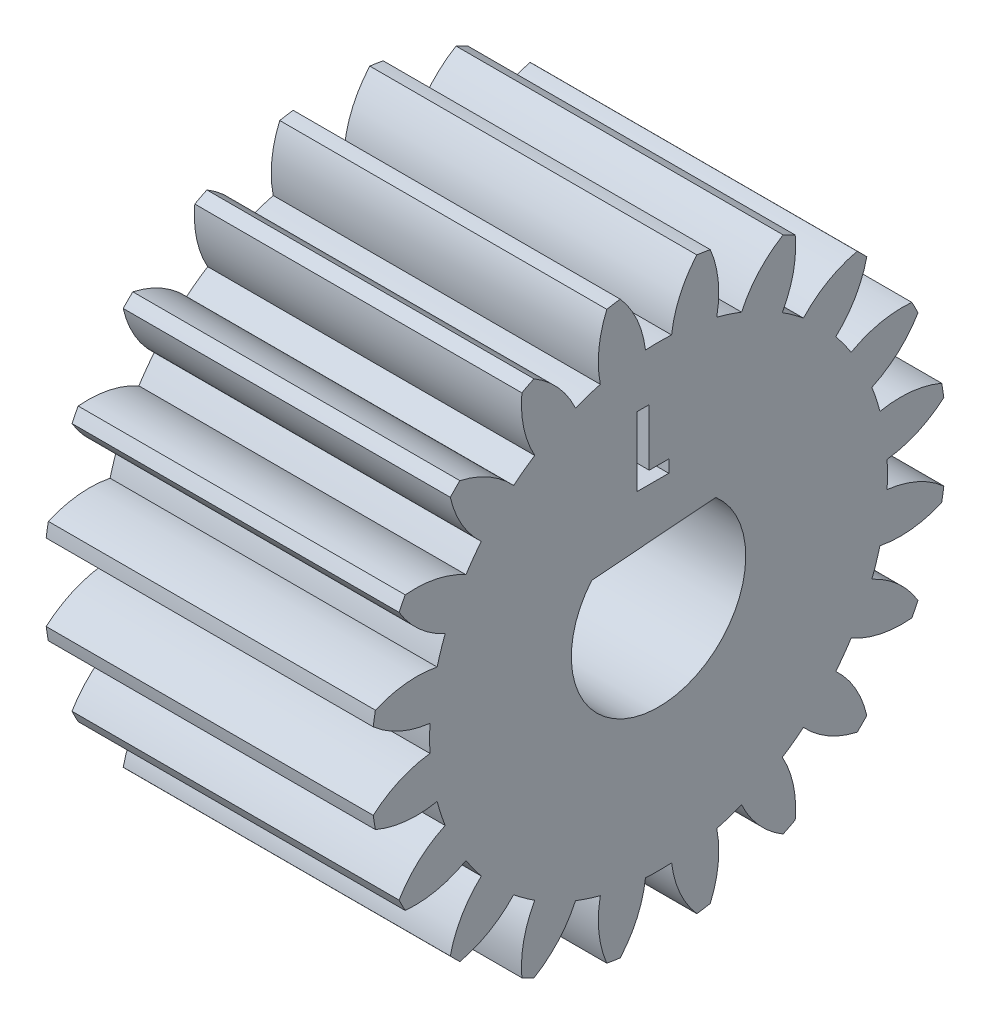
SolidWorks part; units mm, degrees
ref_plane "Plane1" through (0, 0, 0) normal (0, 0, 1) x (1, 0, 0)
ref_plane "Plane2" through (0, 0, 0) normal (0, 1, 0) x (1, 0, 0)
ref_plane "Plane3" through (0, 0, 0) normal (1, 0, 0) x (0, 0, -1)
sketch "HoldingSke" plane through (0, 0, 0) normal (0, 1, 0) x (1, 0, 0)
  line L0 (0, 0) -> (0.7831, -0.285)
  line L1 (-15, 0) -> (100, 0) construction
  line L2 (0, 0) -> (-2.1039, 2.3779)
  line L3 (0, 0) -> (-11.863, 4.5341)
  line L4 (0, 0) -> (8.1152, 2.9537)
  line L5 (0, 0) -> (-46.8476, -17.4728)
  line L6 (0, 0) -> (-12.4344, -8.3896)
  line L7 (-2.1039, 2.3779) -> (8.6586, 51.2059)
  line L8 (-76.2, 54.61) -> (-74.8, 54.61)
  line L9 (-71.009, 38.7566) -> (-53.1078, 45.2721)
  line L10 (-76.2, 71.12) -> (104.1128, 71.12)
  line L11 (0, 0) -> (-15, 0)
  line L12 (-76.2, 101.6) -> (-76.155, 101.6)
  line L13 (24.9733, 27.94) -> (52.9518, 28.4284)
  line L14 (24.9733, 27.94) -> (24.9743, 27.94)
  line L15 (24.9733, 27.94) -> (100.4006, 29.5858)
  line L16 (-63.627, -1.2) -> (-12.827, -1.2)
  circle A0 centre (0, 0) radius 4
  circle A1 centre (0, 0) radius 10.499
  circle A2 centre (0, 0) radius 37.5
  circle A3 centre (0, 0) radius 4
  dimension "MHD" = 20.998
  dimension "Hub_dia" = 75
  dimension "Bore" = 8
  dimension "MBD" = 8
  dimension "Num_teeth" = 20
  dimension "Pitch" = 0.8333
  dimension "Overall_len" = 50
  dimension "Show_teeth" = 20
  dimension "Thickness" = 15
  dimension "OAL" = 50.0001
  dimension "T_dim" = 1.4
  dimension "Ap" = 20
  dimension "H" = 19.05
  dimension "Pitch_radius" = 180.3128
  dimension "Width" = 15
  dimension "Backlash" = 0.045
  dimension "Addendum_fac" = 1
  dimension "Dedendum_fac" = 1.25
  dimension "Clearance_fac" = 0.25
  dimension "Dedendum_add" = 0.001
  dimension "Module" = 1.2
sketch "BasProSke" plane through (0, 0, 0) normal (0, 1, 0) x (1, 0, 0)
  line L0 (-10, 0) -> (60, 0) construction
  line L1 (0, 0) -> (0, 13.2)
  line L2 (0, 0) -> (15, 0)
  line L3 (15, 0) -> (15, 13.2)
  line L4 (15, 13.2) -> (0, 13.2)
  dimension "Thickness" = 15
  dimension "Diameter" = 26.4
revolve "Base-Revolve" add sketch "BasProSke" angle 360 about L0
sketch "TooCutSke" plane through (0, 0, 0) normal (1, 0, 0) x (0, 0, -1)
  line L1 (0, 0) -> (0, 107) construction
  line L2 (0, 0) -> (-1.0202, 11.9566) construction
  line L3 (0, 0) -> (-3.7447, 23.6432) construction
  line L4 (-1.0202, 11.9566) -> (-1.8724, 11.8216) construction
  arc A0 (0.599, 10.4819) -> (-0.599, 10.4819) centre (0, 0) ccw
  arc A1 (1.777, 13.1055) -> (-1.777, 13.1055) centre (0, 0) ccw
  circle A2 centre (0, 0) radius 12 construction
  circle A3 centre (0, 0) radius 11.2763 construction
  arc A4 (-0.599, 10.4819) -> (-1.777, 13.1055) centre (-5.3658, 9.9179) ccw
  arc A5 (1.777, 13.1055) -> (0.599, 10.4819) centre (5.3658, 9.9179) ccw
  dimension "Root_dia" = 20.998
  dimension "Overcut_dia" = 26.4508
  dimension "Pitch_dia" = 24
  dimension "Base_dia" = 22.5526
  dimension "Flank_rad" = 4.8
  dimension "Half_ang" = 9
  dimension "Half_CT" = 0.8628
extrude "ToothCut" cut sketch "TooCutSke" along normal through all
fillet "Breaks" [suppressed] radius 0.024
fillet "RootFillets" [suppressed] radius 0.301
pattern_circular "TeethCuts" count 20 every 18 about axis through (-10, 0, 0) along (1, 0, 0) of "ToothCut", "RootFillets", "Breaks"
sketch "HubNeaOneSke" plane through (0, 0, 0) normal (-1, 0, 0) x (0, 0, 1)
  circle A0 centre (0, 0) radius 10.499
  dimension "Diameter" = 20.998
extrude "HubNearOne" [suppressed] add sketch "HubNeaOneSke" along normal blind 35.0001
sketch "HubNeaBotSke" plane through (0, 0, 0) normal (-1, 0, 0) x (0, 0, 1)
  circle A0 centre (0, 0) radius 10.499
  dimension "Diameter" = 20.998
extrude "HubNearBoth" [suppressed] add sketch "HubNeaBotSke" along normal blind 17.5
ref_plane "FarPln" through (15, 0, 0) normal (1, 0, 0) x (0, 0, -1)
sketch "HubFarSke" plane through (15, 0, 0) normal (1, 0, 0) x (0, 0, -1)
  circle A0 centre (0, 0) radius 10.499
  dimension "Diameter" = 20.998
extrude "HubFar" [suppressed] add sketch "HubFarSke" along normal blind 17.5
sketch "BorSke" plane through (0, 0, 0) normal (1, 0, 0) x (0, 0, -1)
  circle A0 centre (0, 0) radius 4
  dimension "Diameter" = 8
extrude "Bore" cut sketch "BorSke" along normal mid plane 100.0001
sketch "KeySke" plane through (0, 0, 0) normal (1, 0, 0) x (0, 0, -1)
  line L0 (-1.5, 0) -> (-1.5, 5.4)
  line L1 (-1.5, 5.4) -> (1.5, 5.4)
  line L2 (1.5, 5.4) -> (1.5, 0)
  line L3 (0, 0) -> (0, 34) construction
  line L4 (-1.5, 0) -> (1.5, 0)
  dimension "Offset" = 5.4
  dimension "Width" = 3
extrude "Keyway" [suppressed] cut sketch "KeySke" along normal mid plane 100.0001
pattern_circular "Keyway2" [suppressed] count 2 every 90 about axis through (-10, 0, 0) along (1, 0, 0)
sketch "Sketch1" plane through (0, 0, 0) normal (-1, 0, 0) x (0, 0, 1)
  line L0 (0, 0) -> (0, 8) construction
  line L1 (0, 0) -> (0.2197, 2.7914) construction
  line L2 (0.2197, 2.7914) -> (0.3138, 3.9877) construction
  line L3 (3.0675, 2.5672) -> (-2.6281, 3.0155)
  circle A0 centre (0, 0) radius 4 construction
  circle A1 centre (0, 0) radius 8 construction
  circle A2 centre (0, 0) radius 4 construction
  arc A3 (3.0675, 2.5672) -> (-2.6281, 3.0155) centre (0, 0) ccw
  point P12 (0.2197, 2.7914)
  dimension "D1" = 16
  dimension "D2" = 1.2
  dimension "D3" = 4.5
extrude "Boss-Extrude1" add sketch "Sketch1" against normal up to surface (15 mm away) up to face at (15, 0, 4)
sketch "Sketch2" plane through (0, 0, 0) normal (-1, 0, 0) x (0, 0, 1)
  circle A0 centre (0, 0) radius 6
  circle A1 centre (0, 0) radius 7.2
  dimension "D1" = 12
  dimension "D2" = 14.4
extrude "Cut-Extrude1" cut sketch "Sketch2" against normal blind 0.5
sketch "Sketch3" plane through (15, 0, 0) normal (1, 0, 0) x (0, 0, -1)
  text T0 "L" font "Century Gothic" height in points 12
extrude "Cut-Extrude2" cut sketch "Sketch3" against normal blind 2
equation "' \"Module@HoldingSke\" = 6.35"
equation "' \"Num_teeth@HoldingSke\" = 12"
equation "' \"Ap@HoldingSke\" =  20"
equation "' \"Ap@HoldingSke\" = 20"
equation "' \"Width@HoldingSke\" = 0.5 * 25.4"
equation "' \"Hub_dia@HoldingSke\"= 1 * 25.4"
equation "' \"Hub_dia@HoldingSke\" = 1 * 25.4"
equation "' \"Overall_len@HoldingSke\" = 1.0 * 25.4"
equation "' \"Bore@HoldingSke\" = 0.75 * 25.4"
equation "' \"T_dim@HoldingSke\" = 0.1 * 25.4"
equation "' \"Width@KeySke\" = 0.25 * 25.4"
equation "' \"Show_teeth@HoldingSke\" = 13"
equation "' \"Backlash@HoldingSke\" = 0.009 * 25.4"
equation "' \"Addendum_fac@HoldingSke\" = 1.0"
equation "' \"Dedendum_fac@HoldingSke\" = 1.25"
equation "' \"Dedendum_add@HoldingSke\" = 0.00005 * 25.4"
equation "' \"Clearance_fac@HoldingSke\" = 0.25"
equation "\"Pitch@HoldingSke\" = 1 / \"Module@HoldingSke\""
equation "\"Overcut_dia@TooCutSke\" = (\"Num_teeth@HoldingSke\" + 2 * \"Addendum_fac@HoldingSke\") / \"Pitch@HoldingSke\" + 0.002 * 25.4"
equation "\"Pitch_dia@TooCutSke\" = \"Num_teeth@HoldingSke\" / \"Pitch@HoldingSke\""
equation "\"Base_dia@TooCutSke\" = \"Num_teeth@HoldingSke\" / \"Pitch@HoldingSke\" * cos((\"Ap@HoldingSke\"  * 3.14159265 / 180))"
equation "\"Root_dia@TooCutSke\" = (\"Num_teeth@HoldingSke\" + 2) / \"Pitch@HoldingSke\" - 2 * (\"Addendum_fac@HoldingSke\" + \"Dedendum_fac@HoldingSke\") / \"Pitch@HoldingSke\" - \"Dedendum_add@HoldingSke\" * 2"
equation "\"Half_ang@TooCutSke\" = 180 / \"Num_teeth@HoldingSke\""
equation "\"Half_CT@TooCutSke\" = \"Num_teeth@HoldingSke\" / \"Pitch@HoldingSke\" * sin((3.14159265 / 2 / \"Num_teeth@HoldingSke\")) / 2 - 7 * \"Backlash@HoldingSke\" / 4"
equation "\"Flank_rad@TooCutSke\" = \"Num_teeth@HoldingSke\" / \"Pitch@HoldingSke\" / 5"
equation "\"Radius@RootFillets\" = \"Clearance_fac@HoldingSke\" / \"Pitch@HoldingSke\" + \"Dedendum_add@HoldingSke\""
equation "\"Break_rad@Breaks\" = 0.02 / \"Pitch@HoldingSke\""
equation "\"Thickness@HoldingSke\" = \"Width@HoldingSke\""
equation "\"OAL@HoldingSke\" = \"Thickness@HoldingSke\""
equation "\"MHD@HoldingSke\" = (\"Num_teeth@HoldingSke\" + 2) / \"Pitch@HoldingSke\" - 2 * (\"Addendum_fac@HoldingSke\" + \"Dedendum_fac@HoldingSke\")  / \"Pitch@HoldingSke\" - \"Dedendum_add@HoldingSke\" * 2"
equation "\"MBD@HoldingSke\" = (\"Num_teeth@HoldingSke\" + 2) / \"Pitch@HoldingSke\" - 2 * (\"Addendum_fac@HoldingSke\" + \"Dedendum_fac@HoldingSke\")  / \"Pitch@HoldingSke\" - \"Dedendum_add@HoldingSke\" * 2 - 0.002 * 25.4"
equation "\"MHD@HoldingSke\" = ((sgn( \"MHD@HoldingSke\" - \"Hub_dia@HoldingSke\" )-1)*( \"MHD@HoldingSke\" - \"Hub_dia@HoldingSke\" ))/-2+ \"Hub_dia@HoldingSke\""
equation "\"MBD@HoldingSke\" = ((sgn( \"MBD@HoldingSke\" - \"Bore@HoldingSke\" )-1)*( \"MBD@HoldingSke\" - \"Bore@HoldingSke\" ))/-2+ \"Bore@HoldingSke\""
equation "\"OAL@HoldingSke\" = ((sgn( \"OAL@HoldingSke\" - \"Overall_len@HoldingSke\" )+1)*( \"OAL@HoldingSke\" - \"Overall_len@HoldingSke\" ))/2 + \"Overall_len@HoldingSke\" + 0.000002 * 25.4"
equation "\"Num_teeth@TeethCuts\" = int( \"Show_teeth@HoldingSke\" ) + 1"
equation "\"Num_teeth@TeethCuts\" = ((sgn( \"Num_teeth@TeethCuts\" - \"Num_teeth@HoldingSke\" )-1)*( \"Num_teeth@TeethCuts\" - \"Num_teeth@HoldingSke\" ))/-2+ \"Num_teeth@HoldingSke\""
equation "\"Num_teeth@TeethCuts\" = ((sgn( \"Num_teeth@TeethCuts\" - 2.0)+1)*( \"Num_teeth@TeethCuts\" - 2.0))/2 +2.0"
equation "\"Angle@TeethCuts\" = 360.0 / \"Num_teeth@HoldingSke\""
equation "\"Diameter@BasProSke\" = (\"Num_teeth@HoldingSke\" + 2 * \"Addendum_fac@HoldingSke\") / \"Pitch@HoldingSke\""
equation "\"Thickness@BasProSke\"  = \"Thickness@HoldingSke\""
equation "' \"Fillet_rad@BasProSke\" =  \"Thickness@HoldingSke\" * 0.05"
equation "' \"Fillet_rad@BasProSke\" = \"Thickness@HoldingSke\" * 0.05"
equation "\"MHD@HoldingSke\" = ((sgn( \"MHD@HoldingSke\" - \"Root_dia@TooCutSke\" )-1)*( \"MHD@HoldingSke\" - \"Root_dia@TooCutSke\" ))/-2+ \"Root_dia@TooCutSke\""
equation "\"Diameter@HubNeaOneSke\" = \"MHD@HoldingSke\""
equation "\"Length@HubNearOne\" = \"OAL@HoldingSke\" - \"Thickness@BasProSke\""
equation "\"Diameter@HubNeaBotSke\" = \"MHD@HoldingSke\""
equation "\"Length@HubNearBoth\" = ( \"OAL@HoldingSke\" - \"Thickness@BasProSke\" ) / 2.0"
equation "\"Thickness@FarPln\" = \"Thickness@BasProSke\""
equation "\"Diameter@HubFarSke\" = \"MHD@HoldingSke\""
equation "\"Length@HubFar\" = ( \"OAL@HoldingSke\" - \"Thickness@BasProSke\" ) / 2.0"
equation "\"Diameter@BorSke\" = \"MBD@HoldingSke\""
equation "\"D1@Bore\" = \"OAL@HoldingSke\" * 2.0"
equation "\"D1@Keyway\" = \"OAL@HoldingSke\" * 2.0"
equation "\"Offset@KeySke\" = \"T_dim@HoldingSke\" + \"MBD@HoldingSke\" / 2.0"
